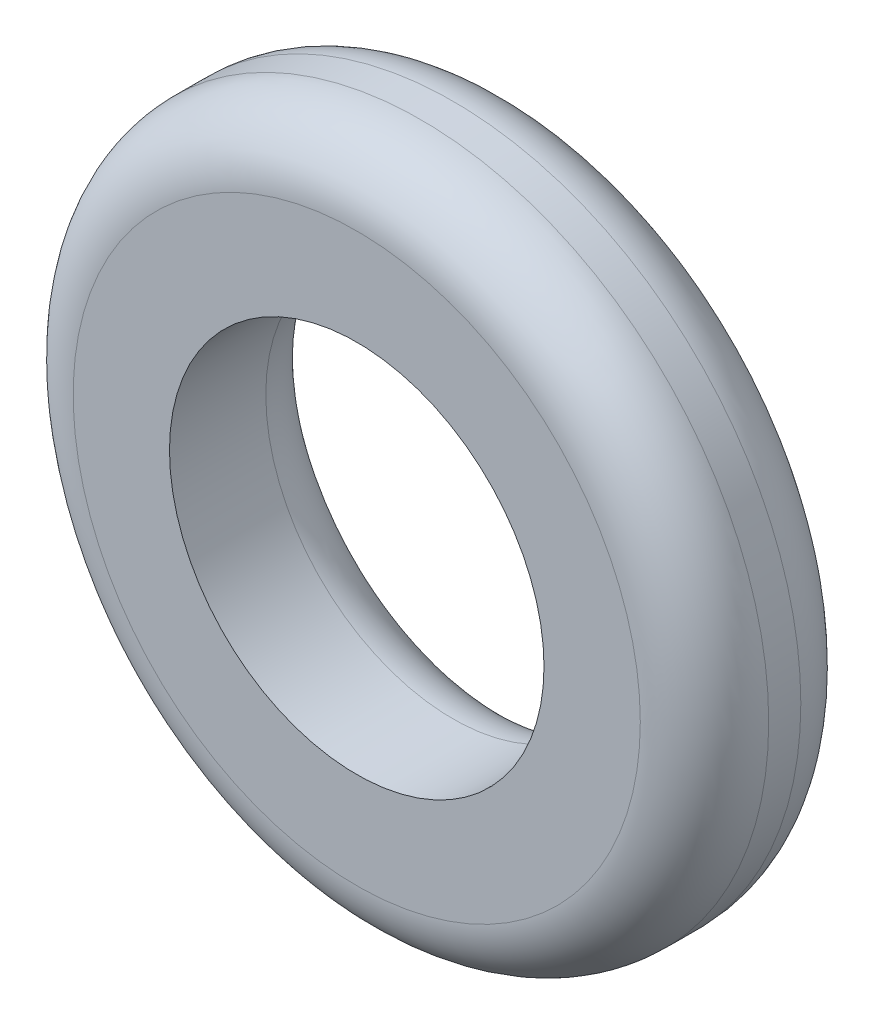
SolidWorks part; units mm, degrees
ref_plane "Front Plane" through (0, 0, 0) normal (0, 0, 1) x (1, 0, 0)
ref_plane "Top Plane" through (0, 0, 0) normal (0, 1, 0) x (1, 0, 0)
ref_plane "Right Plane" through (0, 0, 0) normal (1, 0, 0) x (0, 0, -1)
sketch "Sketch1" plane through (0, 0, 0) normal (0, 0, 1) x (1, 0, 0)
  circle A0 centre (0, 0) radius 1.75
  circle A1 centre (0, 0) radius 3.25
  dimension "D1" = 3.5
  dimension "D2" = 6.5
extrude "Boss-Extrude1" add sketch "Sketch1" along normal blind 1.5
fillet "Fillet1" radius 0.6 3 edges at (1.75, 0, 0) (3.25, 0, 1.5) (3.25, 0, 0)
